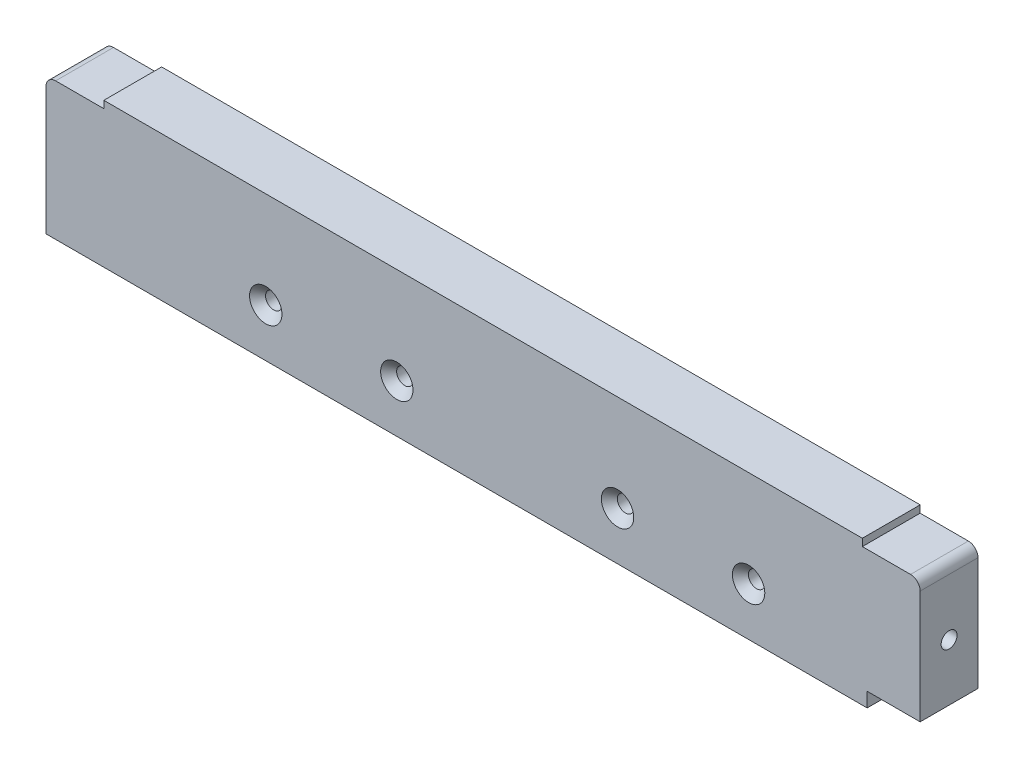
SolidWorks part; units mm, degrees
material "PVC Rígido"
ref_plane "Plano frontal" through (0, 0, 0) normal (0, 0, 1) x (1, 0, 0)
ref_plane "Plano superior" through (0, 0, 0) normal (0, 1, 0) x (1, 0, 0)
ref_plane "Plano direito" through (0, 0, 0) normal (1, 0, 0) x (0, 0, -1)
sketch "Esboço1" plane through (0, 0, 0) normal (0, 0, 1) x (1, 0, 0)
  line L1 (-73.7403, 200) -> (45.2597, 200)
  line L2 (-73.7403, 200) -> (-73.7403, 170)
  line L3 (-73.7403, 170) -> (45.2597, 170)
  line L4 (45.2597, 200) -> (45.2597, 170)
  line L7 (26.4597, 190) -> (45.2597, 190) construction
  dimension "D1" = 30
  dimension "D2" = 119
extrude "Ressalto-extrusão1" add sketch "Esboço1" along normal blind 12
hole_wizard "Escareado para SFHCS M31" positions "Esboço5" profile "Esboço4" countersink size "M3" standard "Métrico Ansi" end condition through all
sketch "Esboço5" plane through (0, 0, 12) normal (0, 0, 1) x (1, 0, 0)
  line L0 (-73.7403, 200) -> (-73.7403, 170) construction
  line L1 (45.2597, 170) -> (45.2597, 200) construction
  line L2 (-73.7403, 170) -> (45.2597, 170) construction
  point P0 (35.8597, 180)
  point P1 (-64.3403, 180)
  point P10 (-37.1403, 180)
  point P12 (8.6597, 180)
  dimension "D1" = 9.4
  dimension "D2" = 9.4
  dimension "D3" = 10
  dimension "D4" = 10
  dimension "D5" = 10
  dimension "D6" = 10
  dimension "D7" = 36.6
  dimension "D8" = 36.6
sketch "Esboço4" plane through (35.8597, 180, 12) normal (1, 0, 0) x (0, -1, 0)
  line L0 (0, 0) -> (0, 12)
  line L1 (0, 12) -> (1.7, 12)
  line L2 (1.7, 12) -> (1.7, 1.66)
  line L3 (1.7, 1.66) -> (3.36, 0)
  line L5 (3.36, 0) -> (0, 0)
  line L6 (-1.7, 1.66) -> (-3.36, 0) construction
  line L11 (0, -6.35) -> (0, 107.95) construction
  dimension "Thru Hole Dia." = 3.4
  dimension "Thru Hole Depth" = 12
  dimension "Near C'Sink Dia." = 6.72
  dimension "Near C'Sink Angle" = 90
sketch "Esboço6" plane through (0, 0, 0) normal (0, 0, 1) x (1, 0, 0)
  line L1 (-109.9403, 200) -> (-73.7403, 200)
  line L2 (-109.9403, 200) -> (-109.9403, 170)
  line L3 (-109.9403, 170) -> (-73.7403, 170)
  line L4 (-73.7403, 200) -> (-73.7403, 170)
  dimension "D1" = 36.2
extrude "Ressalto-extrusão2" add sketch "Esboço6" along normal blind 12
sketch "Esboço7" plane through (0, 0, 0) normal (0, 0, 1) x (1, 0, 0)
  line L1 (71.4597, 170) -> (45.2597, 170)
  line L2 (71.4597, 170) -> (71.4597, 200)
  line L3 (71.4597, 200) -> (45.2597, 200)
  line L4 (45.2597, 170) -> (45.2597, 200)
  dimension "D1" = 26.2
extrude "Ressalto-extrusão3" add sketch "Esboço7" along normal blind 12
sketch "Esboço8" plane through (0, 200, 0) normal (0, 1, 0) x (1, 0, 0)
  line L0 (71.4597, 0) -> (-109.9403, 0) construction
  line L1 (71.4597, -12) -> (59.4597, -12)
  line L2 (71.4597, -12) -> (71.4597, 0)
  line L3 (71.4597, 0) -> (59.4597, 0)
  line L4 (59.4597, -12) -> (59.4597, 0)
  dimension "D1" = 12
extrude "Corte-extrusão1" cut sketch "Esboço8" against normal blind 1.5
fillet "Filete1" radius 2 1 edges at (71.4597, 198.5, 6)
sketch "Esboço9" plane through (0, 170, 0) normal (0, -1, 0) x (1, 0, 0)
  line L0 (-109.9403, 12) -> (71.4597, 12) construction
  line L1 (71.4597, 0) -> (60.4597, 0)
  line L2 (71.4597, 0) -> (71.4597, 12)
  line L3 (71.4597, 12) -> (60.4597, 12)
  line L4 (60.4597, 0) -> (60.4597, 12)
  dimension "D1" = 11
extrude "Corte-extrusão2" cut sketch "Esboço9" against normal blind 3
hole_wizard "Broca de rosquear para tarraxa de M4x0.71" positions "Esboço11" profile "Esboço10" hole size "M4x0.7" standard "Métrico Ansi"
sketch "Esboço11" plane through (71.4597, 0, 0) normal (1, 0, 0) x (0, 0, -1)
  line L1 (0, 173) -> (-12, 173) construction
  line L3 (-12, 173) -> (-12, 196.5) construction
  point P0 (-6, 184.75)
  dimension "D1" = 11.75
  dimension "D2" = 6
sketch "Esboço10" plane through (71.4597, 184.75, 6) normal (0, 1, 0) x (0, 0, -1)
  line L0 (0, 0) -> (0, 10.9914)
  line L1 (0, 10.9914) -> (1.65, 10)
  line L2 (1.65, 10) -> (1.65, 0)
  line L5 (1.65, 0) -> (0, 0)
  line L10 (0, 10.9914) -> (-1.65, 10) construction
  line L11 (0, -6.35) -> (0, 107.95) construction
  dimension "Hole Dia." = 3.3
  dimension "Hole Depth" = 10
  dimension "Drill Angle" = 118
sketch "Esboço12" plane through (0, 200, 0) normal (0, 1, 0) x (-1, 0, 0)
  line L0 (-59.4597, 0) -> (109.9403, 0) construction
  line L1 (109.9403, 12) -> (97.9403, 12)
  line L2 (109.9403, 12) -> (109.9403, 0)
  line L3 (109.9403, 0) -> (97.9403, 0)
  line L4 (97.9403, 12) -> (97.9403, 0)
  dimension "D1" = 12
extrude "Corte-extrusão3" cut sketch "Esboço12" against normal blind 1.5
fillet "Filete2" radius 2 1 edges at (-109.9403, 198.5, 6)
hole_wizard "Broca de rosquear para tarraxa de M4x0.72" positions "Esboço14" profile "Esboço13" hole size "M4x0.7" standard "Métrico Ansi"
sketch "Esboço14" plane through (-109.9403, 0, 0) normal (-1, 0, 0) x (0, 0, 1)
  line L0 (12, 196.5) -> (12, 170) construction
  line L3 (-136.6, 170) -> (-136.6, 196.5) construction
  line L4 (-124.6, 173) -> (-136.6, 173) construction
  line L6 (-136.6412, 172.8084) -> (11.3588, 172.8084) construction
  point P0 (5.5, 184.5584)
  point P1 (-130.6, 184.75)
  dimension "D1" = 6.5
  dimension "D2" = 11.75
  dimension "D3" = 6
  dimension "D4" = 11.75
sketch "Esboço13" plane through (-109.9403, 184.5584, 5.5) normal (0, 1, 0) x (0, 0, 1)
  line L0 (0, 0) -> (0, 10.9914)
  line L1 (0, 10.9914) -> (1.65, 10)
  line L2 (1.65, 10) -> (1.65, 0)
  line L5 (1.65, 0) -> (0, 0)
  line L10 (0, 10.9914) -> (-1.65, 10) construction
  line L11 (0, -6.35) -> (0, 107.95) construction
  dimension "Hole Dia." = 3.3
  dimension "Hole Depth" = 10
  dimension "Drill Angle" = 118
cosmetic thread "Representação de rosca2" parameters "D2"=4
